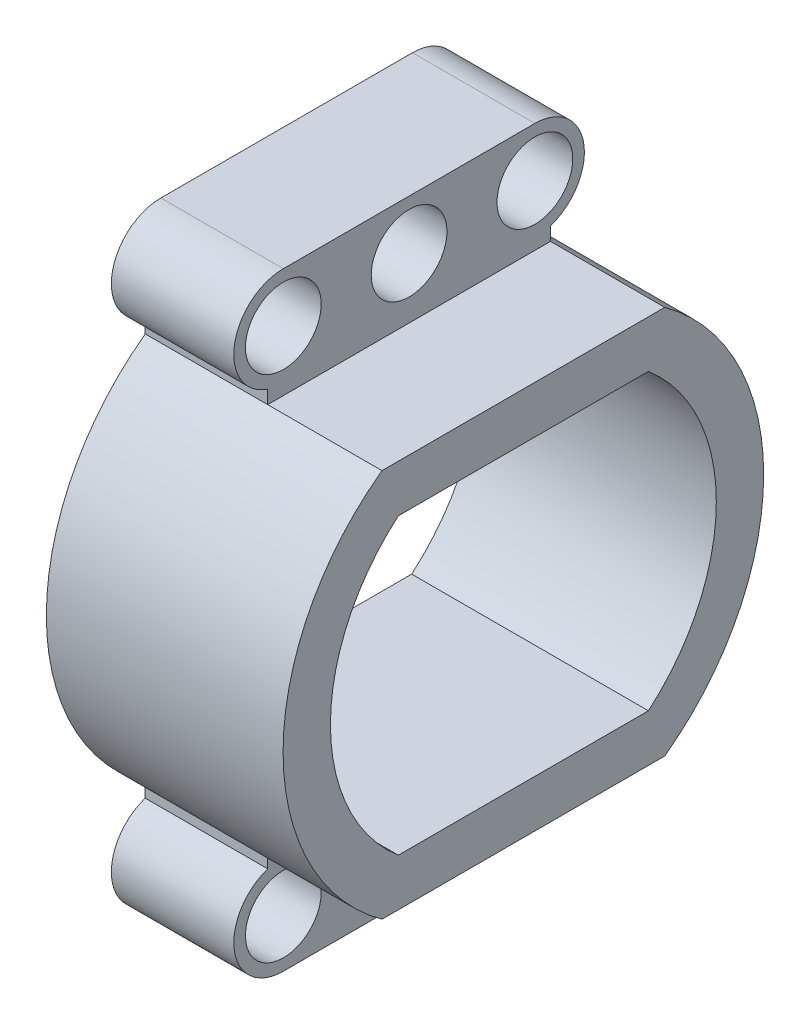
SolidWorks part; units mm, degrees
ref_plane "Front Plane" through (0, 0, 0) normal (0, 0, 1) x (1, 0, 0)
ref_plane "Top Plane" through (0, 0, 0) normal (0, 1, 0) x (1, 0, 0)
ref_plane "Right Plane" through (0, 0, 0) normal (1, 0, 0) x (0, 0, -1)
sketch "Sketch1" plane through (0, 0, 0) normal (1, 0, 0) x (0, 0, -1)
  line L0 (-7.8677, -9.16) -> (7.8677, -9.16) construction
  line L1 (-7.8677, 9.16) -> (7.8677, 9.16) construction
  line L2 (-7.8677, -9.16) -> (7.8677, 9.16) construction
  line L3 (-7.8677, 9.16) -> (7.8677, -9.16) construction
  line L4 (-7.923, 9.31) -> (7.923, 9.31)
  line L5 (-7.923, -9.31) -> (7.923, -9.31)
  line L6 (-8.959, 12.31) -> (8.959, 12.31)
  line L7 (-8.959, -12.31) -> (8.959, -12.31)
  arc A0 (-7.8677, 9.16) -> (-7.8677, -9.16) centre (0, 0) ccw construction
  arc A1 (7.8677, -9.16) -> (7.8677, 9.16) centre (0, 0) ccw construction
  arc A2 (7.923, -9.31) -> (7.923, 9.31) centre (0, 0) ccw
  arc A3 (-7.923, 9.31) -> (-7.923, -9.31) centre (0, 0) ccw
  arc A4 (8.959, -12.31) -> (8.959, 12.31) centre (0, 0) ccw
  arc A5 (-8.959, 12.31) -> (-8.959, -12.31) centre (0, 0) ccw
  point P0 (0, 0)
  point P6 (0, 0)
  dimension "D2" = 24.15
  dimension "D1" = 18.32
  dimension "D3" = 0.15
  dimension "D4" = 3
extrude "Motor Holder" add sketch "Sketch1" along normal blind 15
sketch "Sketch2" plane through (0, 0, 0) normal (-1, 0, 0) x (0, 0, 1)
  line L0 (-7.97, 12.31) -> (-7.97, 19.2773) construction
  line L1 (-7.97, 19.2773) -> (7.97, 19.2773)
  line L2 (7.97, 19.2773) -> (7.97, 12.31) construction
  line L3 (-8.959, 12.31) -> (8.959, 12.31) construction
  line L4 (-7.97, 16.14) -> (7.97, 16.14) construction
  line L5 (0, 0) -> (-9.5877, 0) construction
  line L6 (-7.97, -16.14) -> (7.97, -16.14) construction
  line L7 (7.97, -19.2773) -> (7.97, -12.31) construction
  line L8 (-7.97, -12.31) -> (-7.97, -19.2773) construction
  line L9 (-7.97, -19.2773) -> (7.97, -19.2773)
  line L12 (-8.959, 12.31) -> (-8.959, 13.1627)
  line L13 (8.959, 12.31) -> (8.959, 13.1627)
  line L14 (-8.959, 12.31) -> (8.959, 12.31)
  line L15 (-8.959, -12.31) -> (-8.959, -13.1627)
  line L16 (8.959, -12.31) -> (8.959, -13.1627)
  line L17 (-8.959, -12.31) -> (8.959, -12.31)
  circle A0 centre (-7.97, 16.14) radius 2.4
  circle A1 centre (0, 16.14) radius 2.4
  circle A2 centre (7.97, 16.14) radius 2.4
  arc A3 (-7.97, 19.2773) -> (-8.959, 13.1627) centre (-7.97, 16.14) ccw
  arc A4 (8.959, 13.1627) -> (7.97, 19.2773) centre (7.97, 16.14) ccw
  arc A5 (-7.97, -19.2773) -> (-8.959, -13.1627) centre (-7.97, -16.14) cw
  arc A6 (8.959, -13.1627) -> (7.97, -19.2773) centre (7.97, -16.14) cw
  circle A7 centre (7.97, -16.14) radius 2.4
  circle A8 centre (0, -16.14) radius 2.4
  circle A9 centre (-7.97, -16.14) radius 2.4
  dimension "D2" = 4.8
  dimension "D1" = 32.28
  dimension "D3" = 7.97
  dimension "D4" = 7.97
extrude "Lego Mount" add sketch "Sketch2" against normal blind 7.76
